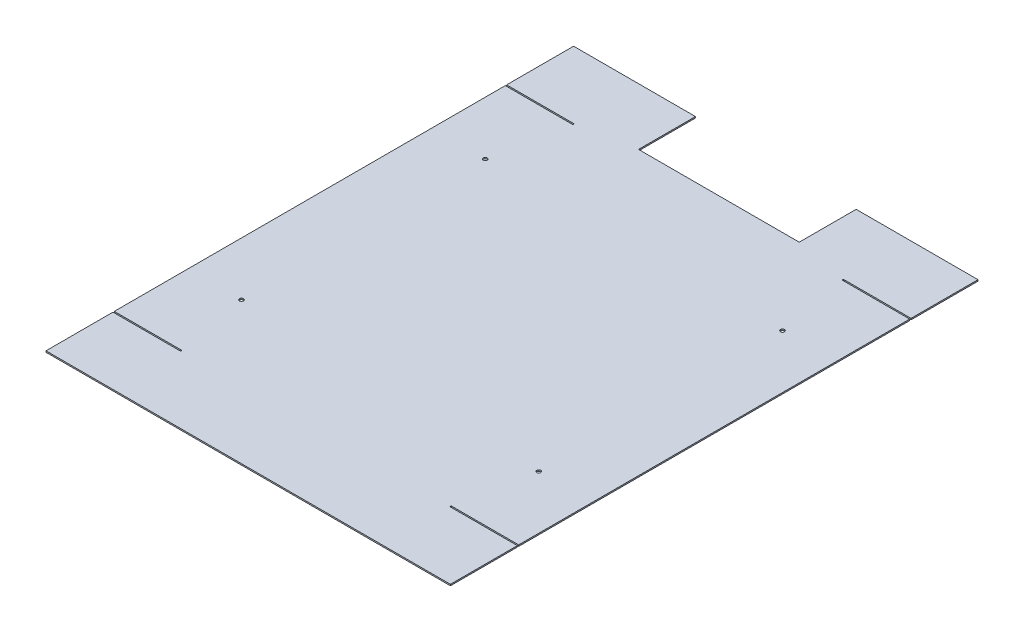
SolidWorks part; units mm, degrees
ref_plane "Front Plane" through (0, 0, 0) normal (0, 0, 1) x (1, 0, 0)
ref_plane "Top Plane" through (0, 0, 0) normal (0, 1, 0) x (1, 0, 0)
ref_plane "Right Plane" through (0, 0, 0) normal (1, 0, 0) x (0, 0, -1)
sketch "Sketch1" plane through (0, 0, 0) normal (0, 1, 0) x (1, 0, 0)
  line L1 (-151, 197) -> (151, 197)
  line L2 (-151, 197) -> (-151, -197)
  line L3 (-151, -197) -> (151, -197)
  line L4 (151, 197) -> (151, -197)
  line L5 (-151, 197) -> (151, -197) construction
  line L6 (-151, -197) -> (151, 197) construction
  point P0 (0, 0)
  dimension "D1" = 302
  dimension "D2" = 394
extrude "Boss-Extrude1" add sketch "Sketch1" along normal blind 1
sketch "Sketch3" plane through (0, 1, 0) normal (0, 1, 0) x (1, 0, 0)
  line L0 (-151, 146.5) -> (-101, 146.5) construction
  line L1 (-151, 197) -> (-151, -197) construction
  line L2 (-151, 147) -> (-101, 147)
  line L3 (-151, 146) -> (-101, 146)
  line L5 (151, 197) -> (-151, 197) construction
  arc A0 (-151, 147) -> (-151, 146) centre (-151, 146.5) ccw
  arc A1 (-101, 146) -> (-101, 147) centre (-101, 146.5) ccw
  point P4 (-126, 146.5)
  dimension "D3" = 50
  dimension "D1" = 1
  dimension "D2" = 50
extrude "Cut-Extrude2" cut sketch "Sketch3" against normal through all
mirror "Mirror1" about plane through (0, 0, 0) normal (0, 0, 1) of "Cut-Extrude2"
mirror "Mirror2" about plane through (0, 0, 0) normal (1, 0, 0) of "Mirror1", "Cut-Extrude2"
sketch "Sketch4" plane through (0, 1, 0) normal (0, 1, 0) x (1, 0, 0)
  line L0 (-151, 146) -> (-151, -146) construction
  line L1 (-151, 146) -> (-101, 146) construction
  circle A0 centre (-111, 91) radius 1.5
  dimension "D1" = 3
  dimension "D3" = 55
  dimension "D2" = 40
  dimension "D4" = 91
extrude "Cut-Extrude3" cut sketch "Sketch4" against normal through all
mirror "Mirror3" about plane through (0, 0, 0) normal (1, 0, 0) of "Cut-Extrude3"
mirror "Mirror4" about plane through (0, 0, 0) normal (0, 0, 1) of "Mirror3", "Cut-Extrude3"
sketch "Sketch5" plane through (0, 1, 0) normal (0, 1, 0) x (1, 0, 0)
  line L0 (0, 205.3585) -> (0, 80.632) construction
  line L1 (151, 197) -> (-151, 197) construction
  line L2 (-60, 154.5) -> (60, 154.5)
  line L3 (-60, 154.5) -> (-60, 197)
  line L4 (-60, 197) -> (60, 197)
  line L5 (60, 154.5) -> (60, 197)
  line L6 (-60, 154.5) -> (60, 197) construction
  line L7 (-60, 197) -> (60, 154.5) construction
  point P3 (0, 175.75)
  dimension "D1" = 120
  dimension "D2" = 42.5
extrude "Cut-Extrude4" cut sketch "Sketch5" against normal through all
